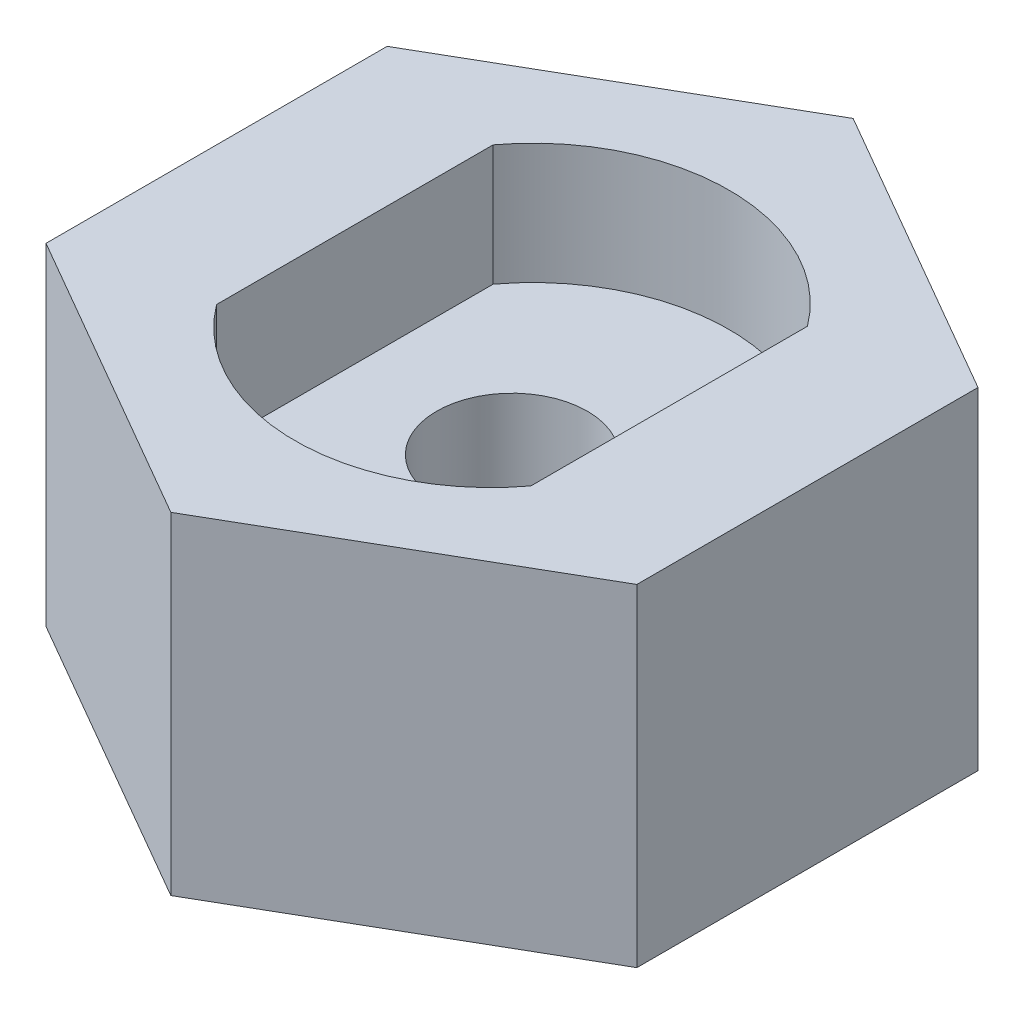
SolidWorks part; units mm, degrees
ref_plane "Front Plane" through (0, 0, 0) normal (0, 0, 1) x (1, 0, 0)
ref_plane "Top Plane" through (0, 0, 0) normal (0, 1, 0) x (1, 0, 0)
ref_plane "Right Plane" through (0, 0, 0) normal (1, 0, 0) x (0, 0, -1)
sketch "Sketch1" plane through (0, 0, 0) normal (0, 1, 0) x (1, 0, 0)
  line L6 (0, 0) -> (-5.875, 0) construction
  line L7 (0, 0) -> (5.875, 0) construction
  line L8 (-5.875, 3.3919) -> (-5.875, -3.3919)
  line L9 (5.875, 3.3919) -> (5.875, -3.3919)
  line L10 (-5.875, 3.3919) -> (0, 6.7839)
  line L11 (0, 6.7839) -> (5.875, 3.3919)
  line L12 (-5.875, -3.3919) -> (0, -6.7839)
  line L13 (0, -6.7839) -> (5.875, -3.3919)
  line L14 (-2.9375, 5.0879) -> (0, 0) construction
  line L15 (0, 0) -> (2.9375, -5.0879) construction
  line L16 (2.9375, 5.0879) -> (0, 0) construction
  line L17 (0, 0) -> (-2.9375, -5.0879) construction
  dimension "D1" = 11.75
extrude "Boss-Extrude1" add sketch "Sketch1" along normal blind 6.6
sketch "Sketch2" plane through (0, 6.6, 0) normal (0, 1, 0) x (1, 0, 0)
  line L2 (3.125, 0) -> (-3.125, 0) construction
  line L3 (-3.125, 2.75) -> (-3.125, -2.75)
  line L4 (3.125, 2.75) -> (3.125, -2.75)
  arc A10 (-3.125, 2.75) -> (3.125, 2.75) centre (0, 0.4167) cw
  arc A12 (-3.125, -2.75) -> (3.125, -2.75) centre (0, -0.4167) ccw
  dimension "D7" = 3.9
  dimension "D1" = 6.25
  dimension "D2" = 3.125
  dimension "D3" = 2.75
  dimension "D4" = 5.5
  dimension "D5" = 5.5
  dimension "D6" = 2.75
extrude "Cut-Extrude1" cut sketch "Sketch2" against normal blind 2.4 contours L3 A12 L4 A10
hole_wizard "Ø3.0mm Dowel Hole1" positions "Sketch3" profile "Sketch4" hole size "Ø3.0" standard "ANSI Metric" end condition through all
sketch "Sketch3" plane through (0, 0, 0) normal (0, -1, 0) x (-1, 0, 0)
  point P0 (0, 0)
sketch "Sketch4" plane through (0, 0, 0) normal (1, 0, 0) x (0, 0, -1)
  line L0 (0, 0) -> (0, 6.6)
  line L1 (0, 6.6) -> (1.5, 6.6)
  line L2 (1.5, 6.6) -> (1.5, 0)
  line L5 (1.5, 0) -> (0, 0)
  line L11 (0, -6.35) -> (0, 107.95) construction
  dimension "Thru Hole Dia." = 3
  dimension "Thru Hole Depth" = 6.6
